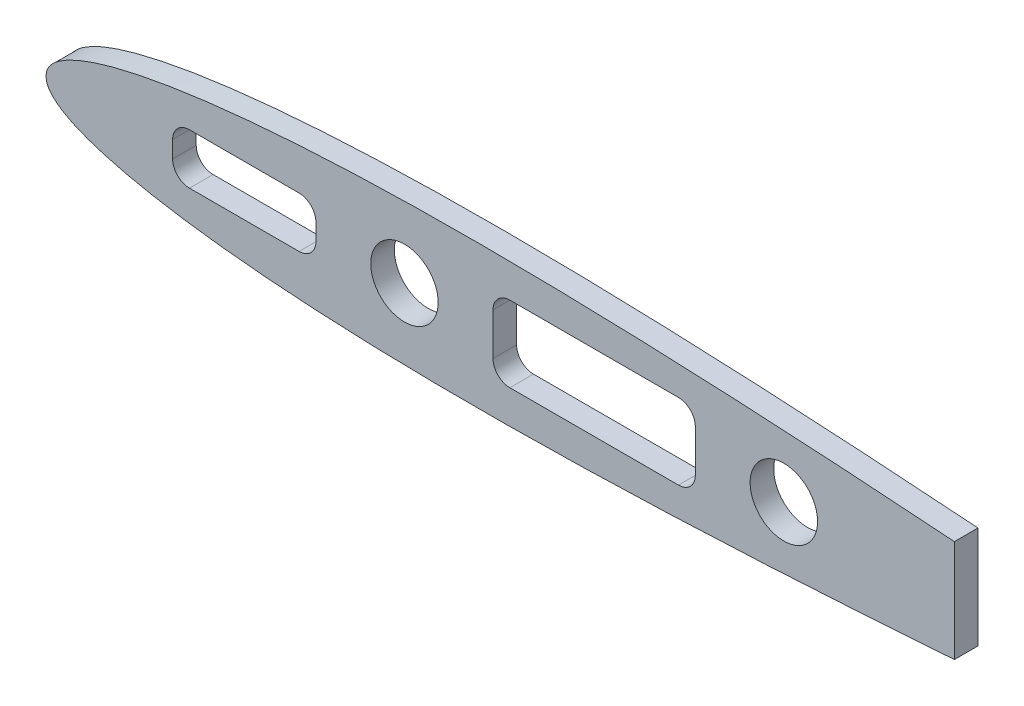
SolidWorks part; units mm, degrees
material "Фанера"
ref_plane "Front Plane" through (0, 0, 0) normal (0, 0, 1) x (1, 0, 0)
ref_plane "Top Plane" through (0, 0, 0) normal (0, 1, 0) x (1, 0, 0)
ref_plane "Right Plane" through (0, 0, 0) normal (1, 0, 0) x (0, 0, -1)
curve "Кривая1"
  spline degree 3 poles (110, 0, 0) (110.0276, -0.2367, 0) (110.0855, -0.7342, 0) (110.5302, -1.4271, 0) (111.1963, -2.0786, 0) (112.1098, -2.7013, 0) (113.2568, -3.2993, 0) (114.6379, -3.8731, 0) (116.2477, -4.4214, 0) (118.0813, -4.9426, 0) (120.1331, -5.4348, 0) (122.3972, -5.8961, 0) (124.8672, -6.3247, 0) (127.537, -6.7187, 0) (130.3997, -7.0764, 0) (133.4488, -7.3965, 0) (136.6771, -7.6776, 0) (140.0777, -7.9187, 0) (143.6433, -8.119, 0) (147.3662, -8.278, 0) (151.2389, -8.3955, 0) (155.2534, -8.4715, 0) (159.4016, -8.5065, 0) (163.6751, -8.501, 0) (168.0653, -8.456, 0) (172.5632, -8.3725, 0) (177.1595, -8.252, 0) (181.8446, -8.096, 0) (186.6087, -7.9062, 0) (191.4413, -7.6846, 0) (196.3316, -7.4331, 0) (201.2684, -7.1538, 0) (206.2396, -6.8489, 0) (211.233, -6.5205, 0) (216.2352, -6.1709, 0) (221.2323, -5.8022, 0) (226.2093, -5.417, 0) (231.1504, -5.0174, 0) (236.0382, -4.6058, 0) (240.8542, -4.1849, 0) (245.5777, -3.7574, 0) (250.1862, -3.3262, 0) (254.6542, -2.8948, 0) (258.9526, -2.4672, 0) (263.0477, -2.0479, 0) (266.899, -1.6426, 0) (270.4558, -1.2586, 0) (273.6512, -0.9053, 0) (276.3854, -0.5964, 0) (278.4526, -0.359, 0) (279.592, -0.2261, 0) (280, -0.1785, 0) knots 0 0 0 0 0.004099 0.008615 0.013935 0.020278 0.027753 0.03641 0.046266 0.05732 0.069559 0.082963 0.097507 0.113164 0.129903 0.14769 0.166492 0.186272 0.206992 0.228612 0.251092 0.274389 0.298458 0.323254 0.348728 0.37483 0.401509 0.42871 0.456376 0.484448 0.512864 0.541558 0.570462 0.599504 0.628607 0.65769 0.686667 0.715445 0.743924 0.771995 0.79954 0.826428 0.852512 0.877624 0.901571 0.924121 0.944989 0.963804 0.980044 0.992855 1 1 1 1
curve "Кривая2"
  spline degree 3 poles (280, 0.1785, 0) (279.592, 0.2261, 0) (278.4526, 0.359, 0) (276.3854, 0.5964, 0) (273.6512, 0.9053, 0) (270.4558, 1.2586, 0) (266.899, 1.6426, 0) (263.0477, 2.0479, 0) (258.9526, 2.4672, 0) (254.6542, 2.8948, 0) (250.1862, 3.3262, 0) (245.5777, 3.7574, 0) (240.8542, 4.1849, 0) (236.0382, 4.6058, 0) (231.1504, 5.0174, 0) (226.2093, 5.417, 0) (221.2323, 5.8022, 0) (216.2352, 6.1709, 0) (211.233, 6.5205, 0) (206.2396, 6.8489, 0) (201.2684, 7.1538, 0) (196.3316, 7.4331, 0) (191.4413, 7.6846, 0) (186.6087, 7.9062, 0) (181.8446, 8.096, 0) (177.1595, 8.252, 0) (172.5632, 8.3725, 0) (168.0653, 8.456, 0) (163.6751, 8.501, 0) (159.4016, 8.5065, 0) (155.2534, 8.4715, 0) (151.2389, 8.3955, 0) (147.3662, 8.278, 0) (143.6433, 8.119, 0) (140.0777, 7.9187, 0) (136.6771, 7.6776, 0) (133.4488, 7.3965, 0) (130.3997, 7.0764, 0) (127.537, 6.7187, 0) (124.8672, 6.3247, 0) (122.3972, 5.8961, 0) (120.1331, 5.4348, 0) (118.0813, 4.9426, 0) (116.2477, 4.4214, 0) (114.6379, 3.8731, 0) (113.2568, 3.2993, 0) (112.1098, 2.7013, 0) (111.1963, 2.0786, 0) (110.5302, 1.4271, 0) (110.0855, 0.7342, 0) (110.0276, 0.2367, 0) (110, 0, 0) knots 0 0 0 0 0.007145 0.019956 0.036196 0.055011 0.075879 0.098429 0.122376 0.147488 0.173572 0.20046 0.228005 0.256076 0.284555 0.313333 0.34231 0.371393 0.400496 0.429538 0.458442 0.487136 0.515552 0.543624 0.57129 0.598491 0.62517 0.651272 0.676746 0.701542 0.725611 0.748908 0.771388 0.793008 0.813728 0.833508 0.85231 0.870097 0.886836 0.902493 0.917037 0.930441 0.94268 0.953734 0.96359 0.972247 0.979722 0.986065 0.991385 0.995901 1 1 1 1
sketch "Эскиз1" plane through (0, 0, 0) normal (0, 0, 1) x (1, 0, 0)
  line L0 (105.1708, 0) -> (280.7263, 0) construction
  line L1 (280.0739, 0) -> (280.0739, 24.3846) construction
  line L2 (110, -5.3315) -> (110, 17.5304) construction
  line L3 (152.5185, 18.8331) -> (152.5185, -21.3473) construction
  line L4 (223.3826, 13.2402) -> (223.3826, -18.4275) construction
  line L5 (217.7476, 6.0581) -> (217.7476, -6.0581)
  line L6 (127.0185, -3) -> (140.0185, -3)
  line L7 (125.0185, -1) -> (125.0185, 1)
  line L8 (127.0185, 3) -> (140.0185, 3)
  line L9 (142.0185, -1) -> (142.0185, 1)
  line L10 (125.0185, -3) -> (142.0185, 3) construction
  line L11 (125.0185, 3) -> (142.0185, -3) construction
  line L12 (165.0185, -4.5) -> (185.0185, -4.5)
  line L13 (163.0185, -2.5) -> (163.0185, 2.5)
  line L14 (165.0185, 4.5) -> (185.0185, 4.5)
  line L15 (187.0185, -2.5) -> (187.0185, 2.5)
  line L16 (163.0185, -4.5) -> (187.0185, 4.5) construction
  line L17 (163.0185, 4.5) -> (187.0185, -4.5) construction
  arc A0 (280, 0.1785) -> (280, -0.1785) centre (279.8215, 0) cw
  circle A1 centre (152.5185, 0) radius 4
  circle A2 centre (197.5185, 0) radius 4
  arc A3 (185.0185, 4.5) -> (187.0185, 2.5) centre (185.0185, 2.5) cw
  arc A4 (185.0185, -4.5) -> (187.0185, -2.5) centre (185.0185, -2.5) ccw
  arc A5 (165.0185, -4.5) -> (163.0185, -2.5) centre (165.0185, -2.5) cw
  arc A6 (163.0185, 2.5) -> (165.0185, 4.5) centre (165.0185, 2.5) cw
  arc A7 (125.0185, 1) -> (127.0185, 3) centre (127.0185, 1) cw
  arc A8 (127.0185, -3) -> (125.0185, -1) centre (127.0185, -1) cw
  arc A9 (140.0185, -3) -> (142.0185, -1) centre (140.0185, -1) ccw
  arc A10 (140.0185, 3) -> (142.0185, 1) centre (140.0185, 1) cw
  arc A11 (223.3826, 5.635) -> (223.3826, -5.635) centre (223.3826, 0) ccw
  circle A12 centre (223.3826, 0) radius 1
  spline S0 degree 3 poles (-3708.6139, -1186.3111) (197.0901, 48.4778) (104.5044, 7.9614) (110.5302, -1.4271) (111.1963, -2.0786) (112.1098, -2.7013) (113.2568, -3.2993) (114.6379, -3.8731) (116.2477, -4.4214) (118.0813, -4.9426) (120.1331, -5.4348) (122.3972, -5.8961) (124.8672, -6.3247) (127.537, -6.7187) (130.3997, -7.0764) (133.4488, -7.3965) (136.6771, -7.6776) (140.0777, -7.9187) (143.6433, -8.119) (147.3662, -8.278) (151.2389, -8.3955) (155.2534, -8.4715) (159.4016, -8.5065) (163.6751, -8.501) (168.0653, -8.456) (172.5632, -8.3725) (177.1595, -8.252) (181.8446, -8.096) (186.6087, -7.9062) (191.4413, -7.6846) (196.3316, -7.4331) (201.2684, -7.1538) (206.2396, -6.8489) (211.233, -6.5205) (216.2352, -6.1709) (221.2323, -5.8022) (226.2093, -5.417) (231.1504, -5.0174) (236.0382, -4.6058) (240.8542, -4.1849) (247.0711, -3.6222) (253.1161, -3.0479) (258.9526, -2.4672) (263.0477, -2.0479) (266.899, -1.6426) (270.4558, -1.2586) (273.6512, -0.9053) (276.3854, -0.5964) (380.7656, 11.3948) (482.347, 39.3944) (1045.8107, -3916.5513) knots -0.174891 -0.174891 -0.174891 -0.174891 0.004099 0.008615 0.013935 0.020278 0.027753 0.03641 0.046266 0.05732 0.069559 0.082963 0.097507 0.113164 0.129903 0.14769 0.166492 0.186272 0.206992 0.228612 0.251092 0.274389 0.298458 0.323254 0.348728 0.37483 0.401509 0.42871 0.456376 0.484448 0.512864 0.541558 0.570462 0.599504 0.628607 0.65769 0.686667 0.715445 0.743924 0.771995 0.79954 0.852512 0.877624 0.901571 0.924121 0.944989 0.963804 0.980044 0.992855 2.791497 2.791497 2.791497 2.791497 only from (110, 0) to (280, -0.1785) construction
  spline S1 degree 3 poles (1045.8012, 3916.4852) (482.3458, -39.3941) (380.765, -11.3948) (276.3854, 0.5964) (273.6512, 0.9053) (270.4558, 1.2586) (266.899, 1.6426) (263.0477, 2.0479) (258.9526, 2.4672) (253.1161, 3.0479) (247.0711, 3.6222) (240.8542, 4.1849) (236.0382, 4.6058) (231.1504, 5.0174) (226.2093, 5.417) (221.2323, 5.8022) (216.2352, 6.1709) (211.233, 6.5205) (206.2396, 6.8489) (201.2684, 7.1538) (196.3316, 7.4331) (191.4413, 7.6846) (186.6087, 7.9062) (181.8446, 8.096) (177.1595, 8.252) (172.5632, 8.3725) (168.0653, 8.456) (163.6751, 8.501) (159.4016, 8.5065) (155.2534, 8.4715) (151.2389, 8.3955) (147.3662, 8.278) (143.6433, 8.119) (140.0777, 7.9187) (136.6771, 7.6776) (133.4488, 7.3965) (130.3997, 7.0764) (127.537, 6.7187) (124.8672, 6.3247) (122.3972, 5.8961) (120.1331, 5.4348) (118.0813, 4.9426) (116.2477, 4.4214) (114.6379, 3.8731) (113.2568, 3.2993) (112.1098, 2.7013) (111.1963, 2.0786) (110.5302, 1.4271) (104.5044, -7.9615) (197.0931, -48.4791) (-3708.8043, 1186.3713) knots -1.791487 -1.791487 -1.791487 -1.791487 0.007145 0.019956 0.036196 0.055011 0.075879 0.098429 0.122376 0.147488 0.20046 0.228005 0.256076 0.284555 0.313333 0.34231 0.371393 0.400496 0.429538 0.458442 0.487136 0.515552 0.543624 0.57129 0.598491 0.62517 0.651272 0.676746 0.701542 0.725611 0.748908 0.771388 0.793008 0.813728 0.833508 0.85231 0.870097 0.886836 0.902493 0.917037 0.930441 0.94268 0.953734 0.96359 0.972247 0.979722 0.986065 0.991385 0.995901 1.174894 1.174894 1.174894 1.174894 only from (280, 0.1785) to (110, 0) construction
  spline S2 degree 3 poles (110, 0) (110.0276, -0.2367) (110.0855, -0.7342) (110.5302, -1.4271) (111.1963, -2.0786) (112.1098, -2.7013) (113.2568, -3.2993) (114.6379, -3.8731) (116.2477, -4.4214) (118.0813, -4.9426) (120.1331, -5.4348) (122.3972, -5.8961) (124.8672, -6.3247) (127.537, -6.7187) (130.3997, -7.0764) (133.4488, -7.3965) (136.6771, -7.6776) (140.0777, -7.9187) (143.6433, -8.119) (147.3662, -8.278) (151.2389, -8.3955) (155.2534, -8.4715) (159.4016, -8.5065) (163.6751, -8.501) (168.0653, -8.456) (172.5632, -8.3725) (177.1595, -8.252) (181.8446, -8.096) (186.6087, -7.9062) (191.4413, -7.6846) (196.3316, -7.4331) (201.2684, -7.1538) (206.2396, -6.8489) (211.233, -6.5205) (216.2352, -6.1709) (221.2323, -5.8022) (226.2093, -5.417) (231.1504, -5.0174) (236.0382, -4.6058) (240.8542, -4.1849) (247.0711, -3.6222) (253.1161, -3.0479) (258.9526, -2.4672) (263.0477, -2.0479) (266.899, -1.6426) (270.4558, -1.2586) (273.6512, -0.9053) (276.3854, -0.5964) (278.4526, -0.359) (279.592, -0.2261) (280, -0.1785) knots 0 0 0 0 0.004099 0.008615 0.013935 0.020278 0.027753 0.03641 0.046266 0.05732 0.069559 0.082963 0.097507 0.113164 0.129903 0.14769 0.166492 0.186272 0.206992 0.228612 0.251092 0.274389 0.298458 0.323254 0.348728 0.37483 0.401509 0.42871 0.456376 0.484448 0.512864 0.541558 0.570462 0.599504 0.628607 0.65769 0.686667 0.715445 0.743924 0.771995 0.79954 0.852512 0.877624 0.901571 0.924121 0.944989 0.963804 0.980044 0.992855 1 1 1 1
  spline S3 degree 3 poles (280, 0.1785) (279.592, 0.2261) (278.4526, 0.359) (276.3854, 0.5964) (273.6512, 0.9053) (270.4558, 1.2586) (266.899, 1.6426) (263.0477, 2.0479) (258.9526, 2.4672) (253.1161, 3.0479) (247.0711, 3.6222) (240.8542, 4.1849) (236.0382, 4.6058) (231.1504, 5.0174) (226.2093, 5.417) (221.2323, 5.8022) (216.2352, 6.1709) (211.233, 6.5205) (206.2396, 6.8489) (201.2684, 7.1538) (196.3316, 7.4331) (191.4413, 7.6846) (186.6087, 7.9062) (181.8446, 8.096) (177.1595, 8.252) (172.5632, 8.3725) (168.0653, 8.456) (163.6751, 8.501) (159.4016, 8.5065) (155.2534, 8.4715) (151.2389, 8.3955) (147.3662, 8.278) (143.6433, 8.119) (140.0777, 7.9187) (136.6771, 7.6776) (133.4488, 7.3965) (130.3997, 7.0764) (127.537, 6.7187) (124.8672, 6.3247) (122.3972, 5.8961) (120.1331, 5.4348) (118.0813, 4.9426) (116.2477, 4.4214) (114.6379, 3.8731) (113.2568, 3.2993) (112.1098, 2.7013) (111.1963, 2.0786) (110.5302, 1.4271) (110.0855, 0.7342) (110.0276, 0.2367) (110, 0) knots 0 0 0 0 0.007145 0.019956 0.036196 0.055011 0.075879 0.098429 0.122376 0.147488 0.20046 0.228005 0.256076 0.284555 0.313333 0.34231 0.371393 0.400496 0.429538 0.458442 0.487136 0.515552 0.543624 0.57129 0.598491 0.62517 0.651272 0.676746 0.701542 0.725611 0.748908 0.771388 0.793008 0.813728 0.833508 0.85231 0.870097 0.886836 0.902493 0.917037 0.930441 0.94268 0.953734 0.96359 0.972247 0.979722 0.986065 0.991385 0.995901 1 1 1 1
  point P19 (175.0185, 0)
  point P22 (133.5185, 0)
  point P31 (223.3826, -5.635)
  point P54 (223.3826, 5.635)
  point P55 (223.3826, -5.635)
  point P56 (223.3826, 5.635)
  point P63 (217.7476, 6.0581)
  point P64 (217.7476, -6.0581)
  dimension "D1" = 0.2524
  dimension "D3" = 8
  dimension "D13" = 2
  dimension "D14" = 5.635
  dimension "D15" = 2
  dimension "D2" = 170.0739
  dimension "D4" = 42.5185
  dimension "D5" = 56.6913
  dimension "D6" = 45
  dimension "D7" = 6
  dimension "D8" = 17
  dimension "D9" = 19
  dimension "D10" = 22.5
  dimension "D11" = 9
  dimension "D12" = 24
extrude "Бобышка-Вытянуть1" add sketch "Эскиз1" along normal mid plane 2.8 contours L5 S3 S2 L8 A10 L9 A9 L6 A8 L7 A7 L13 A6 L14 A3 L15 A4 L12 A5 A1 A2
equation "\"D4@Эскиз1\"=\"D2@Эскиз1\"/4"
equation "\"D5@Эскиз1\"=\"D2@Эскиз1\"/3"
equation "\"D10@Эскиз1\"=\"D6@Эскиз1\"/2"
